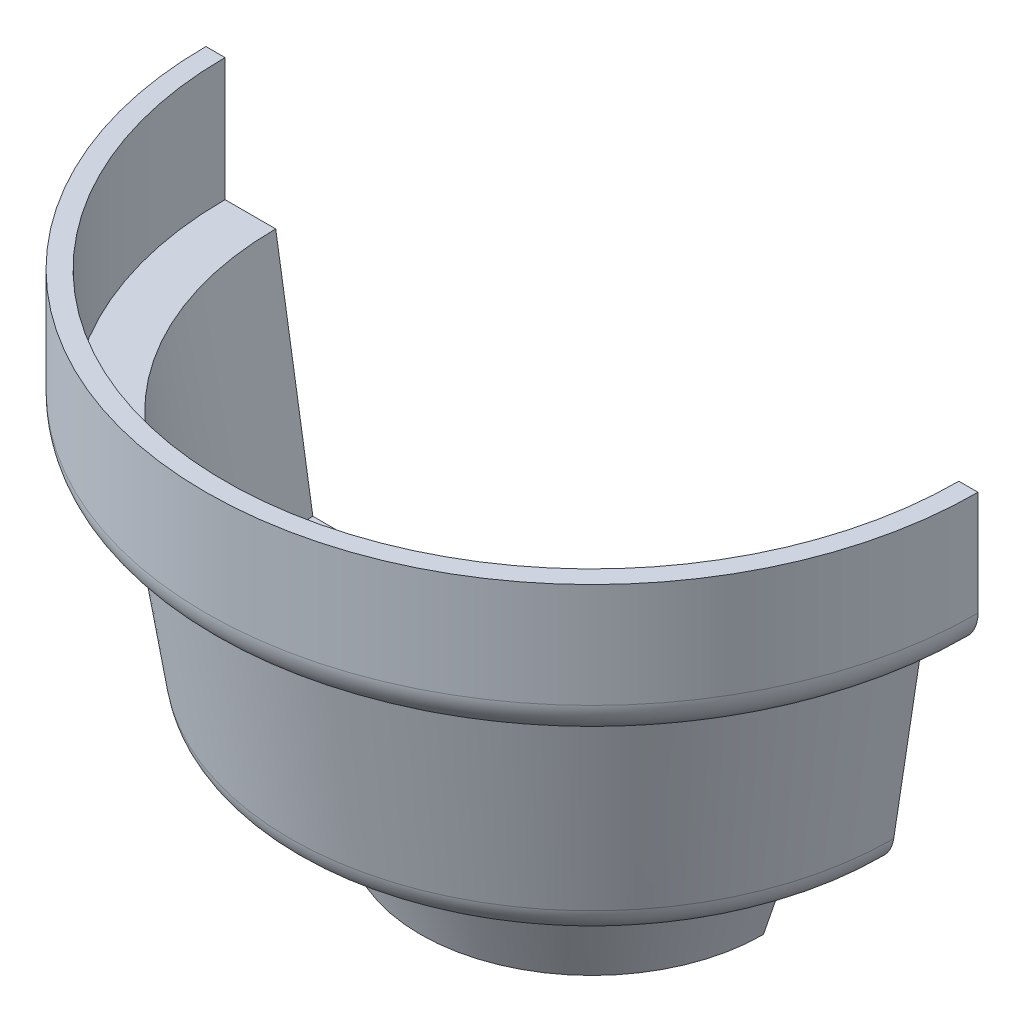
SolidWorks part; units mm, degrees
ref_plane "Front Plane" through (0, 0, 0) normal (0, 0, 1) x (1, 0, 0)
ref_plane "Top Plane" through (0, 0, 0) normal (0, 1, 0) x (1, 0, 0)
ref_plane "Right Plane" through (0, 0, 0) normal (1, 0, 0) x (0, 0, -1)
sketch "Sketch1" plane through (0, 0, 0) normal (0, 0, 1) x (1, 0, 0)
  line L0 (127, 271.5) -> (635, 271.5) construction
  line L2 (298.9844, 58.0411) -> (302.0193, 58.0411)
  line L3 (302.0193, 58.0411) -> (304.0617, 44.7757)
  line L4 (304.0617, 44.7757) -> (308.9326, 44.7757)
  line L5 (308.9326, 44.7757) -> (311.2443, 38.0058)
  line L7 (321.0473, 38.0058) -> (321.0473, 66.0235) construction
  line L10 (300.0781, 66.0235) -> (300.0781, 58.9904)
  line L11 (300.0781, 58.9904) -> (302.974, 58.9904)
  line L12 (302.974, 58.9904) -> (305.0954, 45.8292)
  line L13 (305.0954, 45.8292) -> (308.9326, 45.8292)
  line L14 (308.9326, 45.8292) -> (309.9075, 45.8292)
  line L15 (309.9075, 45.8292) -> (312.0088, 38.9746)
  line L19 (313.9863, 38.9746) -> (313.9863, 38.0058)
  line L20 (312.0088, 38.9746) -> (313.9863, 38.9746)
  line L21 (311.2443, 38.0058) -> (313.9863, 38.0058)
  line L25 (300.0781, 66.0235) -> (298.9844, 66.0235)
  line L26 (298.9844, 66.0235) -> (298.9844, 58.0411)
revolve "Revolve2" add sketch "Sketch1" angle 180 about L7
fillet "Fillet1" radius 2 1 edges at (321.0473, 58.0411, 22.0629)
fillet "Fillet2" radius 2 1 edges at (321.0473, 44.7757, 16.9856)
